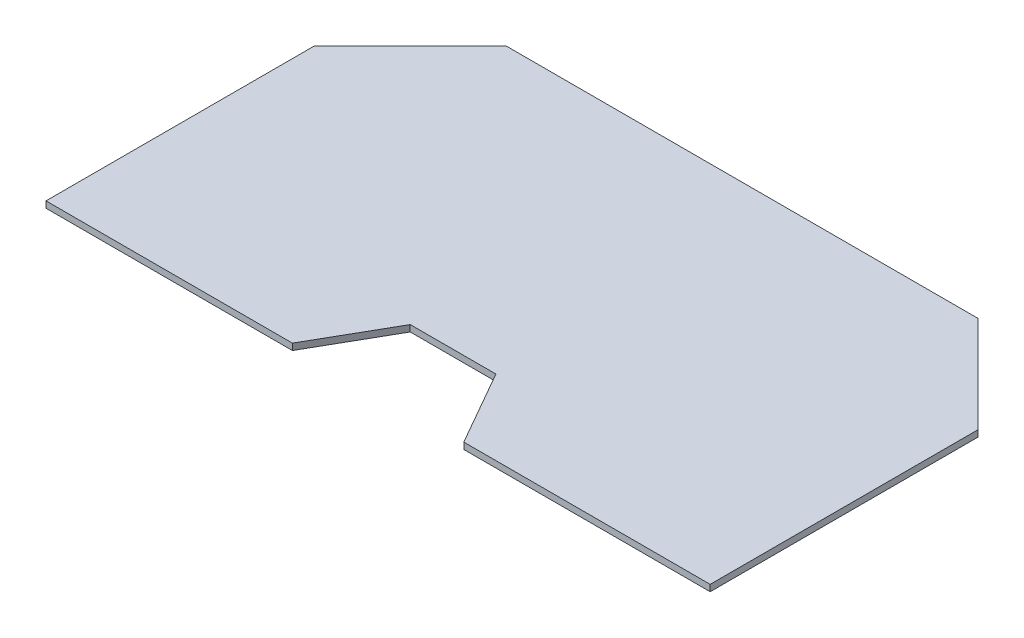
SolidWorks part; units mm, degrees
material "有机玻璃 (TM) GS 丙烯酸铸钣"
ref_plane "前视基准面" through (0, 0, 0) normal (0, 0, 1) x (1, 0, 0)
ref_plane "上视基准面" through (0, 0, 0) normal (0, 1, 0) x (1, 0, 0)
ref_plane "右视基准面" through (0, 0, 0) normal (1, 0, 0) x (0, 0, -1)
sketch "草图1" plane through (0, 0, 0) normal (0, 1, 0) x (1, 0, 0)
  line L1 (-155, -85) -> (155, -85)
  line L2 (-155, -85) -> (-155, 85)
  line L3 (-155, 85) -> (155, 85)
  line L4 (155, -85) -> (155, 85)
  line L5 (-155, -85) -> (155, 85) construction
  line L6 (-155, 85) -> (155, -85) construction
  point P0 (0, 0)
  dimension "D1" = 310
  dimension "D2" = 170
extrude "凸台-拉伸1" add sketch "草图1" along normal blind 3
sketch "草图2" plane through (0, 3, 0) normal (0, 1, 0) x (1, 0, 0)
  line L0 (0, 0) -> (0, -155.5349) construction
  line L1 (-40, -85) -> (-20, -50)
  line L2 (-155, -85) -> (155, -85) construction
  line L3 (40, -85) -> (20, -50)
  line L4 (-20, -50) -> (20, -50)
  dimension "D1" = 80
  dimension "D2" = 35
  dimension "D3" = 40
extrude "切除-拉伸1" cut sketch "草图2" against normal through all and the other way through all
chamfer "倒角1" distance 45 angle 45 2 edges at (155, 1.5, -85) (-155, 1.5, -85)
